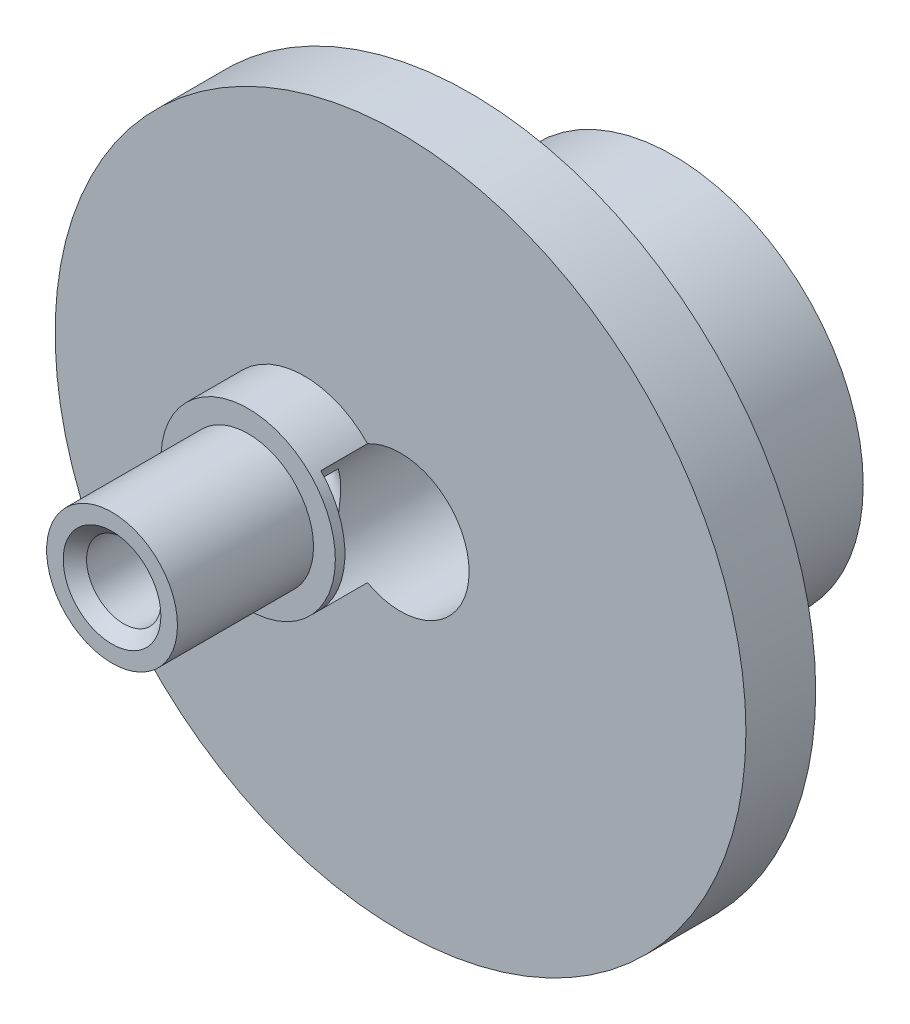
SolidWorks part; units mm, degrees
material "UNS S17400 (17-4)"
ref_plane "Front Plane" through (0, 0, 0) normal (0, 0, 1) x (1, 0, 0)
ref_plane "Top Plane" through (0, 0, 0) normal (0, 1, 0) x (1, 0, 0)
ref_plane "Right Plane" through (0, 0, 0) normal (1, 0, 0) x (0, 0, -1)
sketch "Sketch1" plane through (0, 0, 0) normal (0, 0, 1) x (1, 0, 0)
  circle A0 centre (0, 0) radius 0.127
  circle A1 centre (0, 0) radius 6.9215
  dimension "D1" = 0.254
  dimension "D2" = 13.843
extrude "Boss-Extrude1" add sketch "Sketch1" along normal blind 10.922
sketch "Sketch2" plane through (0, 0, 10.922) normal (0, 0, 1) x (1, 0, 0)
  circle A0 centre (-3.5, 0) radius 2.3813
  dimension "D1" = 4.7625
  dimension "D2" = 3.5
extrude "Boss-Extrude2" add sketch "Sketch2" along normal blind 6.0008
sketch "Sketch4" plane through (0, 0, 10.922) normal (0, 0, 1) x (1, 0, 0)
  circle A1 centre (0, 0) radius 6.9215
  circle A2 centre (0, 0) radius 6.9215
  dimension "D1" = 0
extrude "Boss-Extrude3" add sketch "Sketch4" against normal blind 0.762
sketch "Sketch5" plane through (0, 0, 10.922) normal (0, 0, 1) x (1, 0, 0)
  circle A0 centre (-3.5, 0) radius 3.175
  dimension "D1" = 6.35
extrude "Boss-Extrude4" add sketch "Sketch5" along normal offset from surface (1.0478 mm away) 4.953
hole_wizard "#6-32 Tapped Hole1" positions "Sketch6" profile "Sketch7" tap size "#6-32" standard "ANSI Inch"
sketch "Sketch6" plane through (0, 0, 16.9228) normal (0, 0, 1) x (1, 0, 0)
  point P0 (-3.5, 0)
sketch "Sketch7" plane through (-3.5, 0, 16.9228) normal (1, 0, 0) x (0, -1, 0)
  line L0 (0, 0) -> (0, 7.9247)
  line L1 (0, 7.9247) -> (1.3525, 7.112)
  line L2 (1.3525, 7.112) -> (1.3525, 0.4254)
  line L3 (1.3525, 0.4254) -> (1.778, 0)
  line L5 (1.778, 0) -> (0, 0)
  line L6 (-1.3525, 0.4254) -> (-1.778, 0) construction
  line L10 (0, 7.9247) -> (-1.3525, 7.112) construction
  line L11 (0, -6.35) -> (0, 107.95) construction
  dimension "Tap Drill Dia." = 2.7051
  dimension "Tap Drill Depth" = 7.112
  dimension "Near C'Sink Dia." = 3.556
  dimension "Near C'Sink Angle" = 90
  dimension "Drill Angle" = 118
cosmetic thread "Hole Thread2" parameters "D1"=4.826, "D2"=3.5052
sketch "Sketch8" plane through (0, 0, 0) normal (0, 0, -1) x (-1, 0, 0)
  circle A0 centre (0, 0) radius 3.175
  circle A2 centre (0, 0) radius 6.9215
  circle A3 centre (0, 0) radius 6.9215
  dimension "D1" = 0
  dimension "D2" = 6.35
extrude "Cut-Extrude1" [suppressed] cut sketch "Sketch8" against normal blind 5.715
sketch "Sketch9" plane through (0, 0, 10.16) normal (0, 0, -1) x (-1, 0, 0)
  circle A1 centre (0, 0) radius 0.127
  circle A2 centre (0, 0) radius 0.127
  dimension "D1" = 0
extrude "Cut-Extrude2" cut sketch "Sketch9" against normal through all
sketch "Sketch10" plane through (0, 0, 0) normal (0, 0, -1) x (-1, 0, 0)
  circle A0 centre (0, 0) radius 0.127 construction
  circle A1 centre (0, 0) radius 0.127
  circle A2 centre (0, 0) radius 4
  dimension "D1" = 8
extrude "Boss-Extrude5" [suppressed] add sketch "Sketch10" along normal blind 3.175
sketch "Sketch11" plane through (0, 0, 0) normal (0, 0, -1) x (-1, 0, 0)
  circle A0 centre (0, 0) radius 5.08
  dimension "D1" = 10.16
extrude "Cut-Extrude3" [suppressed] cut sketch "Sketch11" against normal blind 1.778
sketch "Sketch12" plane through (0, 0, 0) normal (0, 0, -1) x (-1, 0, 0)
  circle A2 centre (0, 0) radius 5.7343
extrude "Cut-Extrude4" [suppressed] cut sketch "Sketch12" against normal offset from surface (4.445 mm away) 9.525
sketch "Sketch13" plane through (0, 0, 0) normal (0, 0, -1) x (-1, 0, 0)
  circle A0 centre (0, 0) radius 2.4968
  dimension "D1" = 4.9936
extrude "Cut-Extrude5" cut sketch "Sketch13" against normal offset from surface (11.6205 mm away) 0.6985
sketch "Sketch14" plane through (0, 0, 10.922) normal (0, 0, 1) x (1, 0, 0)
  circle A1 centre (-3.5, 0) radius 3.175
  circle A2 centre (-3.5, 0) radius 3.175
  dimension "D1" = 0
extrude "Cut-Extrude6" [suppressed] cut sketch "Sketch14" against normal blind 0.4445 flip side to cut
sketch "Sketch15" plane through (0, 0, 10.922) normal (0, 0, 1) x (1, 0, 0)
  circle A5 centre (-3.5, 0) radius 3.175
  circle A6 centre (-3.5, 0) radius 3.175
  dimension "D1" = 0
extrude "Cut-Extrude7" cut sketch "Sketch15" against normal blind 1 flip side to cut
sketch "Sketch16" plane through (0, 0, 9.922) normal (0, 0, 1) x (1, 0, 0)
  circle A0 centre (0, 0) radius 12.573
  circle A1 centre (0, 0) radius 6.9215 construction
  circle A2 centre (0, 0) radius 6.9215
  dimension "D1" = 25.146
extrude "Boss-Extrude6" add sketch "Sketch16" against normal blind 2.54
